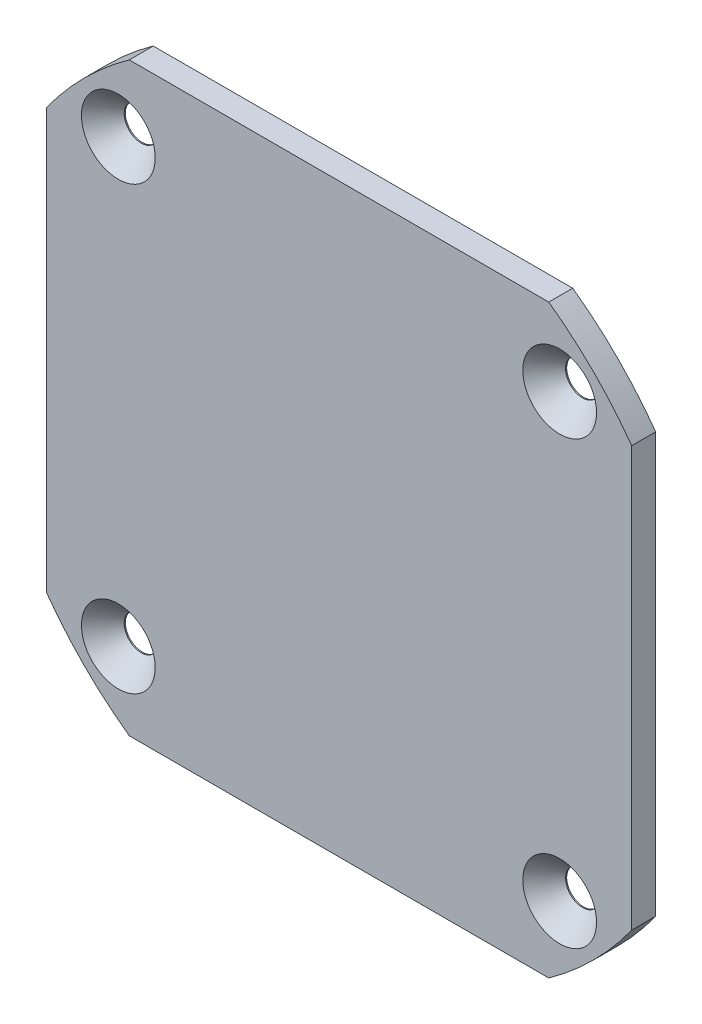
SolidWorks part; units mm, degrees
material "6061-T6 (SS)"
ref_plane "Front Plane" through (0, 0, 0) normal (0, 0, 1) x (1, 0, 0)
ref_plane "Top Plane" through (0, 0, 0) normal (0, 1, 0) x (1, 0, 0)
ref_plane "Right Plane" through (0, 0, 0) normal (1, 0, 0) x (0, 0, -1)
sketch "Sketch1" plane through (0, 0, 0) normal (0, 0, 1) x (1, 0, 0)
  line L0 (-38.1, 0) -> (0, 0) construction
  line L1 (0, 0) -> (-30.48, 30.48) construction
  circle A0 centre (0, 0) radius 38.1 construction
  circle A1 centre (-30.48, 30.48) radius 2.5527 construction
  circle A2 centre (0, 0) radius 47.625
  dimension "D1" = 76.2
  dimension "D2" = 5.1054
  dimension "D4" = 9.525
  dimension "D3" = 45
  dimension "D5" = 30.48
extrude "Boss-Extrude1" add sketch "Sketch1" along normal blind 3.175
hole_wizard "CSK for #8 Flat Head Machine Screw1" positions "Sketch4" profile "Sketch3" countersink size "#8" standard "ANSI Inch" end condition through all
sketch "Sketch4" plane through (0, 0, 3.175) normal (0, 0, 1) x (1, 0, 0)
  line L0 (0, -1000) -> (0, 49000)
  line L1 (29.1858, 29.1858) -> (0, 0)
  circle A0 centre (0, 0) radius 41.275
  point P1 (29.1858, 29.1858)
  dimension "D1" = 82.55
  dimension "D2" = 45
sketch "Sketch3" plane through (29.1858, 29.1858, 3.175) normal (1, 0, 0) x (0, -1, 0)
  line L0 (0, 0) -> (0, 3.175)
  line L1 (0, 3.175) -> (2.2479, 3.175)
  line L2 (2.2479, 3.175) -> (2.2479, 3.0265)
  line L3 (2.2479, 3.0265) -> (4.8788, 0)
  line L5 (4.8788, 0) -> (0, 0)
  line L6 (-2.2479, 3.0265) -> (-4.8788, 0) construction
  line L11 (0, -6.35) -> (0, 107.95) construction
  dimension "Thru Hole Dia." = 4.4958
  dimension "Thru Hole Depth" = 3.175
  dimension "Near C'Sink Dia." = 9.7576
  dimension "Near C'Sink Angle" = 82
pattern_circular "CirPattern1" count 4 over 360 about axis through (0, 0, 0) along (0, 0, 1) of "CSK for #8 Flat Head Machine Screw1"
sketch "Sketch5" plane through (0, 0, 0) normal (0, 0, -1) x (-1, 0, 0)
  circle A0 centre (0, 0) radius 38.1
  dimension "D1" = 76.2
split line "Split Line1"
sketch "Sketch6" plane through (0, 0, 3.175) normal (0, 0, 1) x (1, 0, 0)
  line L1 (-38.7108, 38.7108) -> (38.7108, 38.7108)
  line L2 (-38.7108, 38.7108) -> (-38.7108, -38.7108)
  line L3 (-38.7108, -38.7108) -> (38.7108, -38.7108)
  line L4 (38.7108, 38.7108) -> (38.7108, -38.7108)
  line L5 (-38.7108, 38.7108) -> (38.7108, -38.7108) construction
  line L6 (-38.7108, -38.7108) -> (38.7108, 38.7108) construction
  circle A0 centre (-29.1858, 29.1858) radius 4.8788 construction
  point P0 (0, 0)
  dimension "D1" = 9.525
  dimension "D2" = 9.525
extrude "Cut-Extrude2" cut sketch "Sketch6" against normal through all flip side to cut
